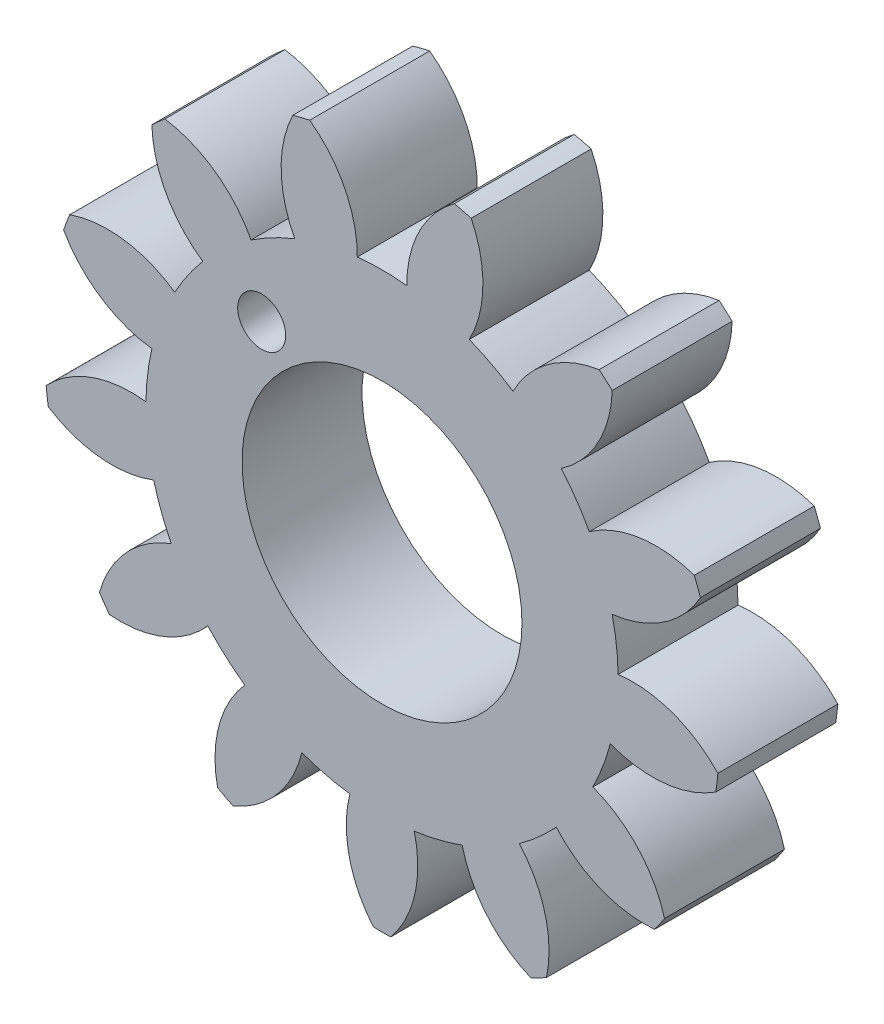
SolidWorks part; units mm, degrees
material "Balsa"
ref_plane "Front Plane" through (0, 0, 0) normal (0, 0, 1) x (1, 0, 0)
ref_plane "Top Plane" through (0, 0, 0) normal (0, 1, 0) x (1, 0, 0)
ref_plane "Right Plane" through (0, 0, 0) normal (1, 0, 0) x (0, 0, -1)
sketch "Sketch1" plane through (0, 0, 0) normal (0, 0, 1) x (1, 0, 0)
  circle A3 centre (2.8747, 12.1494) radius 3.5
  circle A4 centre (-0.1353, 15.427) radius 0.6
  arc A5 (2.2564, 18.0222) -> (1.0675, 20.3911) centre (-0.6685, 18.037) ccw
  arc A6 (1.0675, 20.3911) -> (0.6448, 20.2869) centre (2.8747, 12.1494) ccw
  arc A7 (0.6448, 20.2869) -> (0.6929, 17.6368) centre (3.2759, 19.0092) ccw
  arc A8 (0.6929, 17.6368) -> (-0.402, 17.0622) centre (2.8747, 12.1494) ccw
  arc A9 (5.0565, 17.6368) -> (5.1046, 20.2869) centre (2.4734, 19.0092) ccw
  arc A10 (5.1046, 20.2869) -> (4.6819, 20.3911) centre (2.8747, 12.1494) ccw
  arc A11 (4.6819, 20.3911) -> (3.4929, 18.0222) centre (6.4179, 18.037) ccw
  arc A12 (3.4929, 18.0222) -> (2.2564, 18.0222) centre (2.8747, 12.1494) ccw
  arc A13 (7.3567, 15.9944) -> (8.6308, 18.3185) centre (5.7073, 18.4099) ccw
  arc A14 (8.6308, 18.3185) -> (8.305, 18.6072) centre (2.8747, 12.1494) ccw
  arc A15 (8.305, 18.6072) -> (6.1513, 17.0622) centre (8.7481, 15.716) ccw
  arc A16 (6.1513, 17.0622) -> (5.0565, 17.6368) centre (2.8747, 12.1494) ccw
  arc A17 (8.6301, 13.471) -> (10.8384, 14.9369) centre (8.2922, 16.3765) ccw
  arc A18 (10.8384, 14.9369) -> (10.6841, 15.3439) centre (2.8747, 12.1494) ccw
  arc A19 (10.6841, 15.3439) -> (8.0591, 14.9767) centre (9.7328, 12.5779) ccw
  arc A20 (8.0591, 14.9767) -> (7.3567, 15.9944) centre (2.8747, 12.1494) ccw
  arc A21 (8.5851, 10.645) -> (11.2216, 10.9166) centre (9.6361, 13.3746) ccw
  arc A22 (11.2216, 10.9166) -> (11.2741, 11.3488) centre (2.8747, 12.1494) ccw
  arc A23 (11.2741, 11.3488) -> (8.7792, 12.2436) centre (9.1464, 9.3417) ccw
  arc A24 (8.7792, 12.2436) -> (8.6301, 13.471) centre (2.8747, 12.1494) ccw
  arc A25 (7.2318, 8.1635) -> (9.6926, 7.1788) centre (9.431, 10.0921) ccw
  arc A26 (9.6926, 7.1788) -> (9.9399, 7.5371) centre (2.8747, 12.1494) ccw
  arc A27 (9.9399, 7.5371) -> (8.1466, 9.4888) centre (7.1232, 6.7487) ccw
  arc A28 (8.1466, 9.4888) -> (8.5851, 10.645) centre (2.8747, 12.1494) ccw
  arc A29 (4.8804, 6.5952) -> (6.6017, 4.5797) centre (7.7239, 7.2809) ccw
  arc A30 (6.6017, 4.5797) -> (6.9872, 4.782) centre (2.8747, 12.1494) ccw
  arc A31 (6.9872, 4.782) -> (6.3063, 7.3436) centre (4.1267, 5.3929) ccw
  arc A32 (6.3063, 7.3436) -> (7.2318, 8.1635) centre (2.8747, 12.1494) ccw
  arc A33 (2.0695, 6.2993) -> (2.657, 3.7147) centre (4.9059, 5.585) ccw
  arc A34 (2.657, 3.7147) -> (3.0923, 3.7147) centre (2.8747, 12.1494) ccw
  arc A35 (3.0923, 3.7147) -> (3.6799, 6.2993) centre (0.8434, 5.585) ccw
  arc A36 (3.6799, 6.2993) -> (4.8804, 6.5952) centre (2.8747, 12.1494) ccw
  arc A37 (-0.557, 7.3436) -> (-1.2379, 4.782) centre (1.6226, 5.3929) ccw
  arc A38 (-1.2379, 4.782) -> (-0.8524, 4.5797) centre (2.8747, 12.1494) ccw
  arc A39 (-0.8524, 4.5797) -> (0.8689, 6.5952) centre (-1.9746, 7.2809) ccw
  arc A40 (0.8689, 6.5952) -> (2.0695, 6.2993) centre (2.8747, 12.1494) ccw
  arc A41 (-2.3973, 9.4888) -> (-4.1906, 7.5371) centre (-1.3738, 6.7487) ccw
  arc A42 (-4.1906, 7.5371) -> (-3.9433, 7.1788) centre (2.8747, 12.1494) ccw
  arc A43 (-3.9433, 7.1788) -> (-1.4825, 8.1635) centre (-3.6816, 10.0921) ccw
  arc A44 (-1.4825, 8.1635) -> (-0.557, 7.3436) centre (2.8747, 12.1494) ccw
  arc A45 (-3.0298, 12.2436) -> (-5.5248, 11.3488) centre (-3.397, 9.3417) ccw
  arc A46 (-5.5248, 11.3488) -> (-5.4723, 10.9166) centre (2.8747, 12.1494) ccw
  arc A47 (-5.4723, 10.9166) -> (-2.8357, 10.645) centre (-3.8867, 13.3746) ccw
  arc A48 (-2.8357, 10.645) -> (-2.3973, 9.4888) centre (2.8747, 12.1494) ccw
  arc A49 (-2.3097, 14.9767) -> (-4.9347, 15.3439) centre (-3.9835, 12.5779) ccw
  arc A50 (-4.9347, 15.3439) -> (-5.0891, 14.9369) centre (2.8747, 12.1494) ccw
  arc A51 (-5.0891, 14.9369) -> (-2.8808, 13.471) centre (-2.5429, 16.3765) ccw
  arc A52 (-2.8808, 13.471) -> (-3.0298, 12.2436) centre (2.8747, 12.1494) ccw
  arc A119 (-0.402, 17.0622) -> (-2.5556, 18.6072) centre (-2.9988, 15.716) ccw
  arc A120 (-2.5556, 18.6072) -> (-2.8815, 18.3185) centre (2.8747, 12.1494) ccw
  arc A121 (-2.8815, 18.3185) -> (-1.6073, 15.9944) centre (0.0421, 18.4099) ccw
  arc A122 (-1.6073, 15.9944) -> (-2.3097, 14.9767) centre (2.8747, 12.1494) ccw
  point P98 (2.8747, 12.1494)
  dimension "D1" = 8.4375
  dimension "D2" = 2.925
  dimension "D3" = 5.9053
  dimension "D4" = 1.2365
  dimension "D5" = 1.2
  dimension "D6" = 4.45
  dimension "D7" = 13
extrude "Boss-Extrude1" add sketch "Sketch1" along normal blind 3 contours A3
